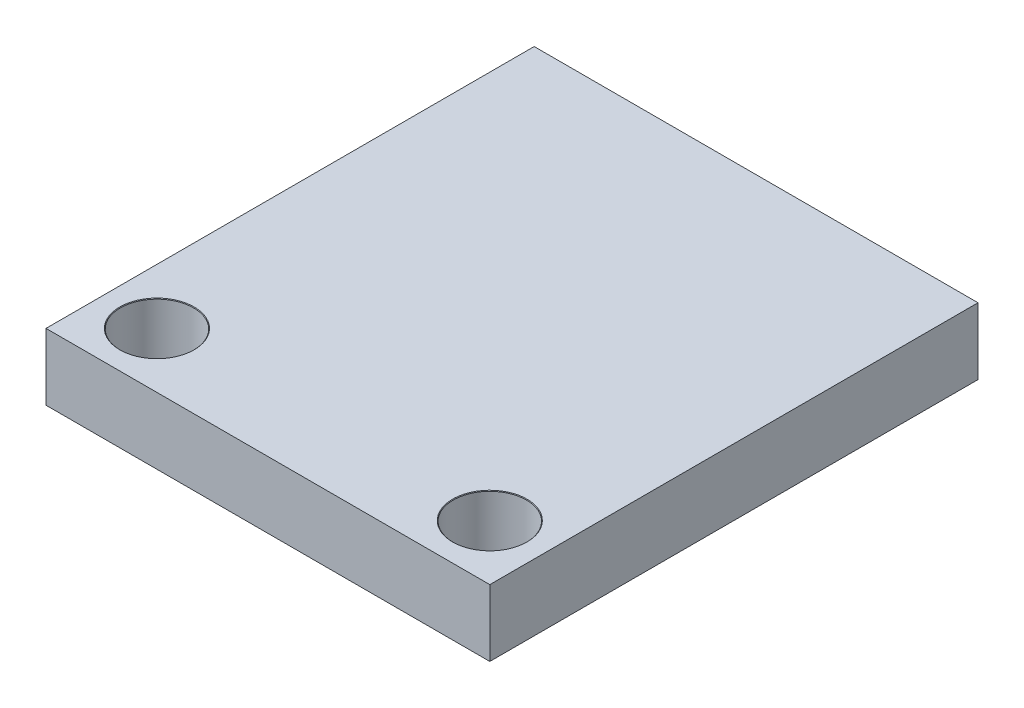
SolidWorks part; units mm, degrees
ref_plane "Front Plane" through (0, 0, 0) normal (0, 0, 1) x (1, 0, 0)
ref_plane "Top Plane" through (0, 0, 0) normal (0, 1, 0) x (1, 0, 0)
ref_plane "Right Plane" through (0, 0, 0) normal (1, 0, 0) x (0, 0, -1)
sketch "Sketch1" plane through (0, 0, 0) normal (0, 1, 0) x (1, 0, 0)
  line L1 (-10, 11) -> (10, 11)
  line L2 (-10, 11) -> (-10, -11)
  line L3 (-10, -11) -> (10, -11)
  line L4 (10, 11) -> (10, -11)
  line L5 (-10, 11) -> (10, -11) construction
  line L6 (-10, -11) -> (10, 11) construction
  point P0 (0, 0)
  dimension "D1" = 20
  dimension "D2" = 22
extrude "Boss-Extrude1" add sketch "Sketch1" along normal blind 3
hole_wizard "Ø3.3 (3.3) Diameter Hole1" positions "Sketch2" profile "Sketch3" hole size "Ø3.3" standard "ISO" end condition through all
sketch "Sketch2" plane through (0, 3, 0) normal (0, 1, 0) x (1, 0, 0)
  line L0 (0, 0) -> (0, -8.5) construction
  line L2 (-7.5, -8.5) -> (7.5, -8.5) construction
  point P6 (-7.5, -8.5)
  point P7 (7.5, -8.5)
  dimension "D1" = 15
  dimension "D2" = 8.5
sketch "Sketch3" plane through (7.5, 3, 8.5) normal (1, 0, 0) x (0, 0, 1)
  line L0 (0, 0) -> (0, 3)
  line L1 (0, 3) -> (1.65, 3)
  line L2 (1.65, 3) -> (1.65, 0.025)
  line L3 (1.65, 0.025) -> (1.675, 0)
  line L5 (1.675, 0) -> (0, 0)
  line L6 (-1.65, 0.025) -> (-1.675, 0) construction
  line L11 (0, -6.35) -> (0, 107.95) construction
  dimension "Thru Hole Dia." = 3.3
  dimension "Thru Hole Depth" = 3
  dimension "Near C'Sink Dia." = 3.35
  dimension "Near C'Sink Angle" = 90
